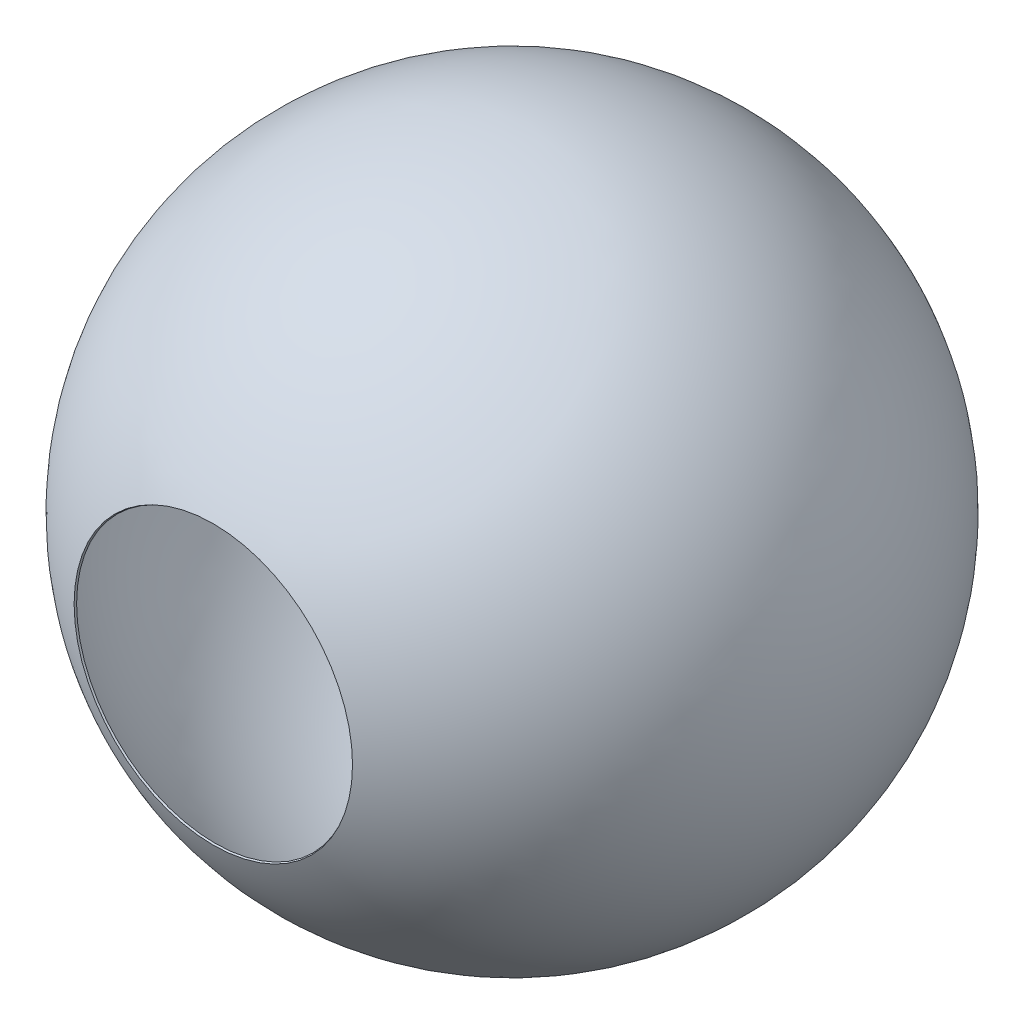
SolidWorks part; units mm, degrees
ref_plane "Front Plane" through (0, 0, 0) normal (0, 0, 1) x (1, 0, 0)
ref_plane "Top Plane" through (0, 0, 0) normal (0, 1, 0) x (1, 0, 0)
ref_plane "Right Plane" through (0, 0, 0) normal (1, 0, 0) x (0, 0, -1)
sketch "Sketch1" plane through (0, 0, 0) normal (1, 0, 0) x (0, 0, -1)
  line L0 (528.5016, 124.6399) -> (528.5016, 0)
  line L3 (-495, 230.6517) -> (-495, 0) construction
  line L4 (-492.1901, 229.3424) -> (0, 0) construction
  line L5 (-495, 230.6517) -> (-492.1901, 229.3424)
  line L6 (-495, 0) -> (531.6016, 0) construction
  line L7 (531.6016, 125) -> (531.6016, 0)
  line L8 (528.5016, 0) -> (531.6016, 0)
  arc A0 (531.6016, 125) -> (-495, 230.6517) centre (0, 0) ccw
  arc A1 (528.5016, 124.6399) -> (-492.1901, 229.3424) centre (0, 0) ccw
  point P2 (0, 0)
  point P8 (0, 0)
  dimension "D1" = 546.1
  dimension "D2" = 543
  dimension "D3" = 495
  dimension "D4" = 125
  dimension "D5" = 3.1
revolve "Shell" add sketch "Sketch1" angle 360 about L6
sketch "Sketch3" plane through (0, 0, 0) normal (0, 0, 1) x (1, 0, 0)
  line L0 (-356.5753, -20.7815) -> (269.657, 26.3052) construction
  line L1 (0, 543) -> (0, -543) construction
  line L2 (0, 0) -> (267.2143, 472.7003) construction
  line L3 (0, 0) -> (-267.2143, 472.7003) construction
  line L4 (-543, 0) -> (543, 0) construction
  line L5 (0, 0) -> (456.9362, -293.357) construction
  line L6 (0, 0) -> (-456.9362, -293.357) construction
  circle A0 centre (0, 0) radius 543
  dimension "D1" = 1086
